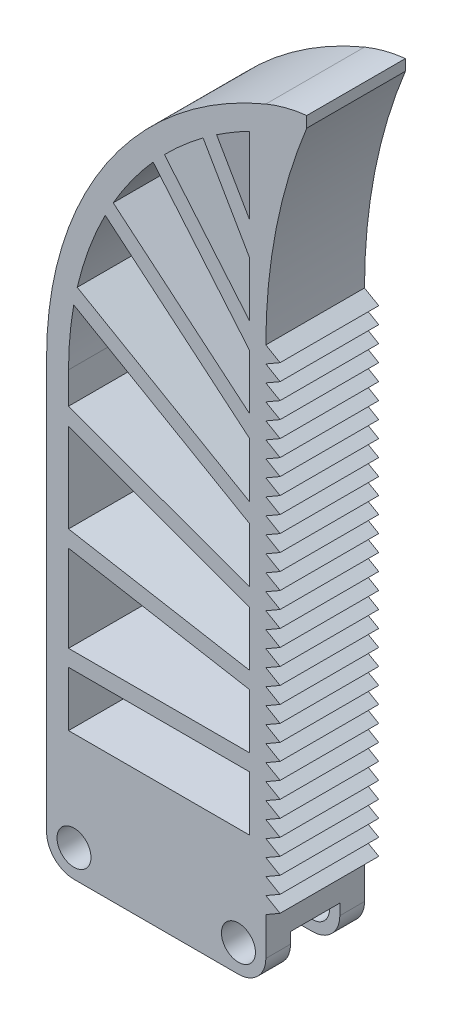
SolidWorks part; units mm, degrees
ref_plane "Front Plane" through (0, 0, 0) normal (0, 0, 1) x (1, 0, 0)
ref_plane "Top Plane" through (0, 0, 0) normal (0, 1, 0) x (1, 0, 0)
ref_plane "Right Plane" through (0, 0, 0) normal (1, 0, 0) x (0, 0, -1)
sketch "Sketch2" plane through (0, 0, 0) normal (0, 0, 1) x (1, 0, 0)
  line L0 (-20, 0) -> (20, 0)
  line L5 (20, 0) -> (20, 140)
  line L10 (-20, 0) -> (-20, 80)
  arc A0 (20, 140) -> (-20, 80) centre (45, 80) ccw
  dimension "D4" = 40
  dimension "D5" = 140
  dimension "D6" = 80
extrude "Boss-Extrude1" add sketch "Sketch2" along normal blind 18
sketch "Sketch3" plane through (0, 0, 18) normal (0, 0, 1) x (1, 0, 0)
  line L0 (-16, 23) -> (17, 23)
  line L1 (17, 23) -> (17, 33)
  line L2 (17, 33) -> (-16, 33)
  line L3 (-16, 33) -> (-16, 23)
  line L4 (-20, 80) -> (-20, 0) construction
  line L5 (20, 0) -> (20, 140) construction
  line L7 (-20, 0) -> (20, 0) construction
  dimension "D1" = 4
  dimension "D2" = 3
  dimension "D3" = 23
  dimension "D4" = 10
sketch "Sketch4" plane through (0, 0, 18) normal (0, 0, 1) x (1, 0, 0)
  line L0 (-16, 36) -> (17, 36)
  line L1 (17, 36) -> (17, 46)
  line L2 (17, 46) -> (-16, 51.8188)
  line L3 (-16, 51.8188) -> (-16, 36)
  line L4 (-20, 80) -> (-20, 0) construction
  line L5 (17, 33) -> (-16, 33) construction
  line L6 (20, 0) -> (20, 140) construction
  dimension "D1" = 4
  dimension "D2" = 3
  dimension "D3" = 3
  dimension "D4" = 10
  dimension "D5" = 10
sketch "Sketch5" plane through (0, 0, 18) normal (0, 0, 1) x (1, 0, 0)
  line L0 (-16, 54.8651) -> (17, 49.0463)
  line L1 (17, 49.0463) -> (17, 59.0463)
  line L2 (17, 59.0463) -> (-16, 71.0573)
  line L3 (-16, 71.0573) -> (-16, 54.8651)
  line L4 (-20, 80) -> (-20, 0) construction
  line L5 (20, 0) -> (20, 140) construction
  line L7 (17, 46) -> (-16, 51.8188) construction
  line L8 (-16, 36) -> (17, 36) construction
  dimension "D1" = 4
  dimension "D2" = 3
  dimension "D3" = 3
  dimension "D4" = 20
  dimension "D5" = 10
sketch "Sketch6" plane through (0, 0, 18) normal (0, 0, 1) x (1, 0, 0)
  line L0 (-16, 74.2498) -> (17, 62.2388)
  line L1 (17, 62.2388) -> (17, 72.2388)
  line L2 (17, 72.2388) -> (-15.0469, 90.7411)
  line L3 (-16, 74.2498) -> (-16, 80)
  line L5 (17, 59.0463) -> (-16, 71.0573) construction
  line L6 (-20, 80) -> (-20, 0) construction
  line L7 (20, 0) -> (20, 140) construction
  line L8 (-16, 36) -> (17, 36) construction
  arc A0 (-15.0469, 90.7411) -> (-16, 80) centre (45, 80) ccw
  arc A2 (20, 140) -> (-20, 80) centre (45, 80) ccw construction
  dimension "D1" = 3
  dimension "D2" = 4
  dimension "D3" = 3
  dimension "D4" = 30
  dimension "D5" = 10
extrude "Cut-Extrude1" cut sketch "Sketch3" against normal through all contours L0 L1 L2 L3
extrude "Cut-Extrude2" cut sketch "Sketch4" against normal through all contours L0 L1 L2 L3
extrude "Cut-Extrude3" cut sketch "Sketch5" against normal through all contours L0 L1 L2 L3
extrude "Cut-Extrude4" cut sketch "Sketch6" against normal through all contours L0 L1 L2 A0 L3
sketch "Sketch13" plane through (0, 0, 18) normal (0, 0, 1) x (1, 0, 0)
  line L0 (20, 0) -> (20, 140) construction
  line L1 (27.4639, 141.9193) -> (27.4639, 139.9193)
  line L2 (20, 140) -> (20, 101.9347)
  arc A0 (20, 140) -> (27.4639, 141.9193) centre (30.3921, 115.059) cw
  arc A1 (20, 101.9347) -> (27.4639, 139.9193) centre (120.3863, 101.9347) cw
  arc A2 (20, 140) -> (-20, 80) centre (45, 80) ccw construction
  dimension "D1" = 2
extrude "Boss-Extrude2" add sketch "Sketch13" against normal up to surface (18 mm away) up to face at (-2.2708, 56.5139, 0)
sketch "Sketch15" plane through (0, 0, 18) normal (0, 0, 1) x (1, 0, 0)
  line L0 (20, 101.9347) -> (22.5981, 100.4347)
  line L1 (22.5981, 100.4347) -> (20, 98.9347)
  line L2 (20, 0) -> (20, 101.9347) construction
  line L3 (20, 101.9347) -> (20, 98.9347)
  dimension "D1" = 3
  dimension "D2" = 3
  dimension "D3" = 3
extrude "Boss-Extrude3" add sketch "Sketch15" against normal up to surface (18 mm away) up to face at (9.1325, 87.2085, 0)
pattern_linear "LPattern1" count 30 spacing 3 along (0, -1, 0) of "Boss-Extrude3"
sketch "Sketch17" plane through (0, 0, 18) normal (0, 0, 1) x (1, 0, 0)
  line L0 (-14.4098, 93.8374) -> (17, 75.7029)
  line L1 (17, 75.7029) -> (17, 85.7029)
  line L2 (17, 85.7029) -> (-9.3082, 107.7781)
  line L3 (17, 72.2388) -> (-15.0469, 90.7411) construction
  line L4 (17, 62.2388) -> (17, 72.2388) construction
  arc A0 (-9.3082, 107.7781) -> (-14.4098, 93.8374) centre (45, 80) ccw
  arc A1 (-15.0469, 90.7411) -> (-16, 80) centre (45, 80) ccw construction
  dimension "D1" = 10
  dimension "D2" = 3
  dimension "D3" = 10
extrude "Cut-Extrude5" cut sketch "Sketch17" against normal through all contours L2 A0 L0 L1
sketch "Sketch18" plane through (0, 0, 18) normal (0, 0, 1) x (1, 0, 0)
  line L0 (-7.8462, 110.4676) -> (17, 89.6191)
  line L1 (17, 89.6191) -> (17, 99.6191)
  line L2 (17, 99.6191) -> (-0.5668, 120.5545)
  line L3 (17, 85.7029) -> (-9.3082, 107.7781) construction
  line L4 (17, 75.7029) -> (17, 85.7029) construction
  arc A0 (-0.5668, 120.5545) -> (-7.8462, 110.4676) centre (45, 80) ccw
  arc A1 (-9.3082, 107.7781) -> (-14.4098, 93.8374) centre (45, 80) ccw construction
  dimension "D1" = 3
  dimension "D2" = 10
  dimension "D3" = 10
extrude "Cut-Extrude6" cut sketch "Sketch18" against normal through all
sketch "Sketch19" plane through (0, 0, 18) normal (0, 0, 1) x (1, 0, 0)
  line L0 (1.4976, 122.7614) -> (17, 104.2863)
  line L1 (17, 104.2863) -> (17, 114.2863)
  line L2 (17, 114.2863) -> (8.554, 128.9151)
  line L3 (17, 89.6191) -> (17, 99.6191) construction
  line L5 (17, 99.6191) -> (-0.5668, 120.5545) construction
  arc A0 (8.554, 128.9151) -> (1.4976, 122.7614) centre (45, 80) ccw
  arc A1 (-0.5668, 120.5545) -> (-7.8462, 110.4676) centre (45, 80) ccw construction
  dimension "D1" = 10
  dimension "D2" = 3
  dimension "D3" = 10
extrude "Cut-Extrude7" cut sketch "Sketch19" against normal through all contours L2 A0 L0 L1
sketch "Sketch21" plane through (0, 0, 18) normal (0, 0, 1) x (1, 0, 0)
  line L0 (11.0136, 130.655) -> (17, 120.2863)
  line L1 (17, 120.2863) -> (17, 134.1941)
  line L3 (17, 114.2863) -> (8.554, 128.9151) construction
  line L4 (17, 104.2863) -> (17, 114.2863) construction
  arc A0 (17, 134.1941) -> (11.0136, 130.655) centre (45, 80) ccw
  arc A1 (8.554, 128.9151) -> (1.4976, 122.7614) centre (45, 80) ccw construction
  dimension "D2" = 3
extrude "Cut-Extrude8" cut sketch "Sketch21" against normal through all
ref_plane "Plane1" through (0, 0, 9) normal (0, 0, -1) x (-1, 0, 0)
sketch "Sketch25" plane through (0, 0, 9) normal (0, 0, -1) x (-1, 0, 0)
  line L0 (-20, 0) -> (-20, 7)
  line L2 (-20, 7) -> (-17, 7)
  line L3 (-13, 3) -> (-13, 0)
  line L4 (20, 0) -> (-20, 0) construction
  line L5 (-13, 0) -> (-20, 0)
  arc A0 (-17, 7) -> (-13, 3) centre (-17, 3) cw
  point P11 (-16.2678, 2.5385)
  dimension "D1" = 3
  dimension "D3" = 4
  dimension "D2" = 7
extrude "Cut-Extrude9" cut sketch "Sketch25" against normal blind 4.5 and the other way blind 4.5
fillet "Fillet1" radius 5 3 edges at (20, 0, 2.25) (20, 0, 15.75) (-20, 0, 9)
hole_wizard "Ø6.0 mm Dowel Holes1" positions "Sketch22" profile "Sketch23" hole size "Ø6.0" standard "ISO" end condition through all
sketch "Sketch22" plane through (0, 0, 18) normal (0, 0, 1) x (1, 0, 0)
  point P0 (-15, 5)
sketch "Sketch23" plane through (-15, 5, 18) normal (1, 0, 0) x (0, -1, 0)
  line L0 (0, 0) -> (0, 18)
  line L1 (0, 18) -> (3.1, 18)
  line L2 (3.1, 18) -> (3.1, 0)
  line L5 (3.1, 0) -> (0, 0)
  line L11 (0, -6.35) -> (0, 107.95) construction
  dimension "Thru Hole Dia." = 6.2
  dimension "Thru Hole Depth" = 18
mirror "Mirror1" about plane through (0, 0, 0) normal (1, 0, 0) of "Ø6.0 mm Dowel Holes1"
